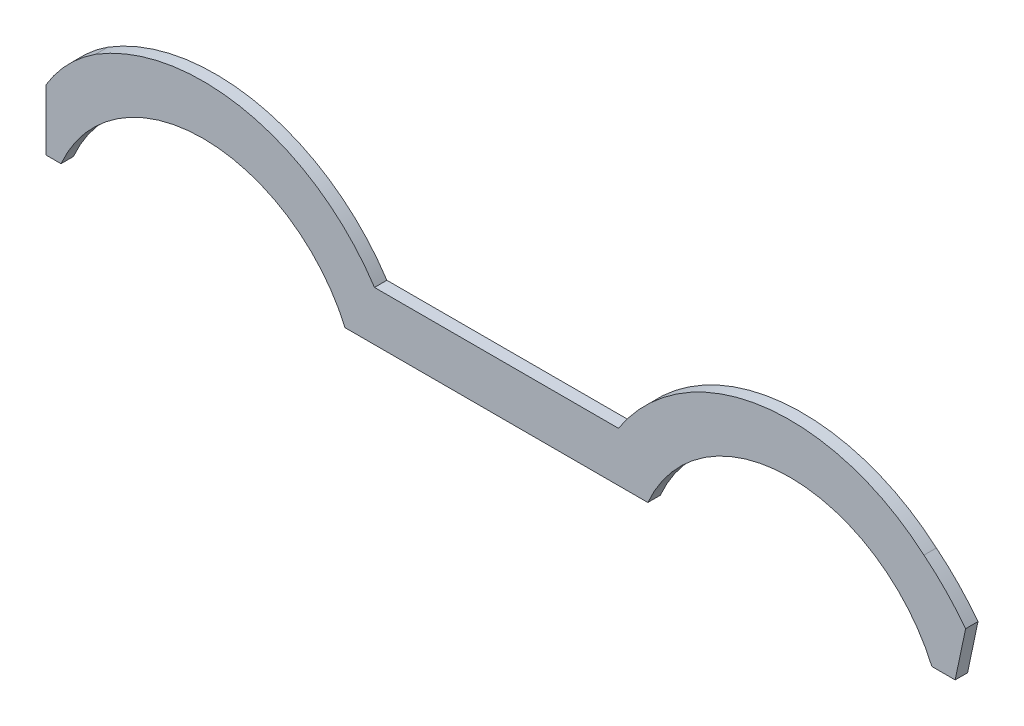
SolidWorks part; units mm, degrees
ref_plane "Front Plane" through (0, 0, 0) normal (0, 0, 1) x (1, 0, 0)
ref_plane "Top Plane" through (0, 0, 0) normal (0, 1, 0) x (1, 0, 0)
ref_plane "Right Plane" through (0, 0, 0) normal (1, 0, 0) x (0, 0, -1)
sketch "Sketch1" plane through (0, 0, 0) normal (0, 0, 1) x (1, 0, 0)
  line L2 (-5.6307, 0) -> (0, 0)
  line L4 (-74.3693, 0) -> (-147.6307, 0)
  line L5 (0, 0) -> (2.5278, 12)
  line L6 (-216.3693, 0) -> (-220, 0)
  line L7 (-220, 0) -> (-220, 14.726)
  line L26 (-140.512, 12) -> (-81.488, 12)
  arc A4 (-208, 27.1218) -> (-220, 14.726) centre (-187.5257, -4.7049) ccw
  arc A5 (-7.5492, 22.3791) -> (2.5278, 12) centre (-44.9702, -24.0343) cw
  arc A8 (-140.512, 12) -> (-208, 27.1218) centre (-182, -15) ccw
  arc A9 (-7.5492, 22.3791) -> (-81.488, 12) centre (-40, -15) ccw
  arc A14 (-147.6307, 0) -> (-216.3693, 0) centre (-182, -15) ccw
  arc A15 (-5.6307, 0) -> (-74.3693, 0) centre (-40, -15) ccw
extrude "Boss-Extrude1" add sketch "Sketch1" along normal blind 3
